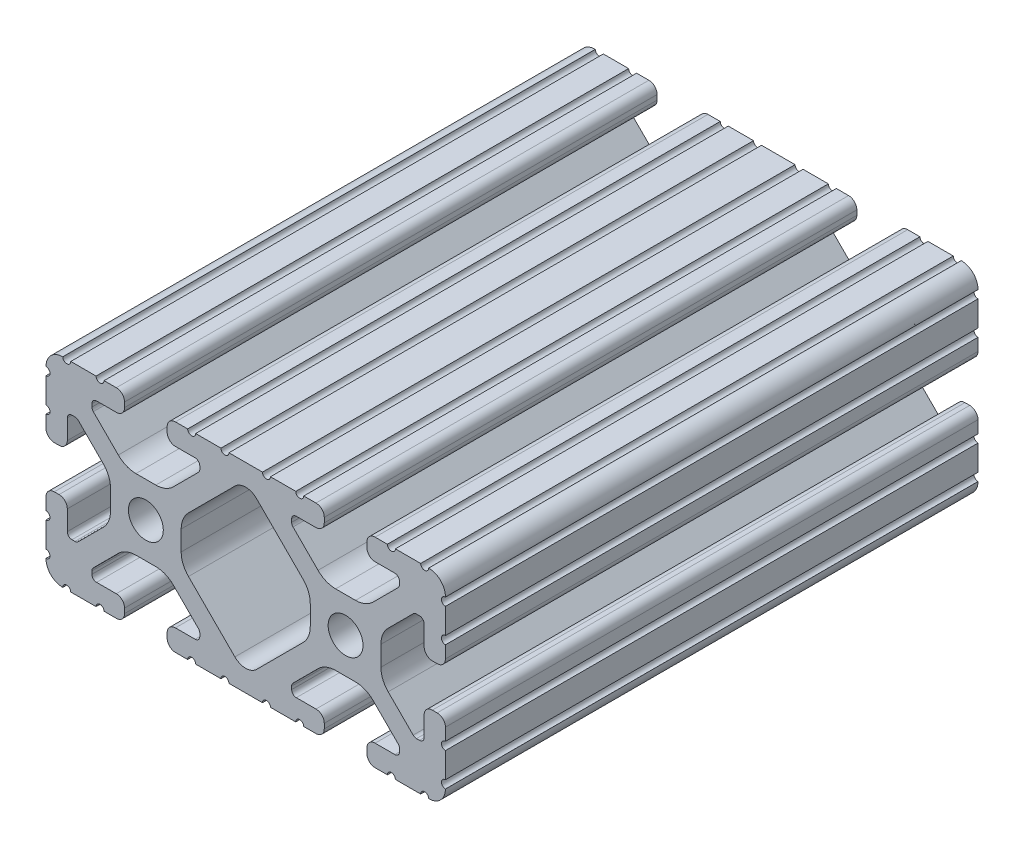
SolidWorks part; units mm, degrees
material "6105-T5 Aluminum"
ref_plane "Front Plane" through (0, 0, 0) normal (0, 0, 1) x (1, 0, 0)
ref_plane "Top Plane" through (0, 0, 0) normal (0, 1, 0) x (1, 0, 0)
ref_plane "Right Plane" through (0, 0, 0) normal (1, 0, 0) x (0, 0, -1)
sketch "Sketch1" plane through (0, 0, 0) normal (0, 0, 1) x (1, 0, 0)
  line L0 (-12.312, -1.8969) -> (-12.312, 1.8969)
  line L1 (-10.9208, 5.2555) -> (-2.0655, 14.1109)
  line L2 (2.0655, 14.1109) -> (10.9208, 5.2555)
  line L3 (12.312, 1.8969) -> (12.312, -1.8969)
  line L4 (10.9208, -5.2555) -> (2.0655, -14.1109)
  line L5 (-2.0655, -14.1109) -> (-10.9208, -5.2555)
  line L6 (38.1, -14.3256) -> (38.1, -9.4996)
  line L7 (38.1, -7.9756) -> (38.1, -5.6388)
  line L8 (36.5252, -4.064) -> (35.6108, -4.064)
  line L9 (34.036, -5.6388) -> (34.036, -9.398)
  line L10 (33.147, -10.287) -> (32.5789, -10.287)
  line L11 (31.9503, -10.0266) -> (27.1792, -5.2555)
  line L12 (25.788, -1.8969) -> (25.788, 1.8969)
  line L13 (27.1792, 5.2555) -> (31.9503, 10.0266)
  line L14 (32.5789, 10.287) -> (33.147, 10.287)
  line L15 (34.036, 9.398) -> (34.036, 5.6388)
  line L16 (35.6108, 4.064) -> (36.5252, 4.064)
  line L17 (38.1, 5.6388) -> (38.1, 7.9756)
  line L18 (38.1, 9.4996) -> (38.1, 14.3256)
  line L19 (38.1, 15.8496) -> (38.1, 15.875)
  line L20 (34.925, 19.05) -> (34.8996, 19.05)
  line L21 (33.3756, 19.05) -> (28.5496, 19.05)
  line L22 (27.0256, 19.05) -> (24.6888, 19.05)
  line L23 (23.114, 17.4752) -> (23.114, 16.5608)
  line L24 (24.6888, 14.986) -> (28.448, 14.986)
  line L25 (29.337, 14.097) -> (29.337, 13.5289)
  line L26 (29.0766, 12.9003) -> (24.3055, 8.1292)
  line L27 (20.9469, 6.738) -> (17.1531, 6.738)
  line L28 (13.7945, 8.1292) -> (9.0234, 12.9003)
  line L29 (8.763, 13.5289) -> (8.763, 14.097)
  line L30 (9.652, 14.986) -> (13.4112, 14.986)
  line L31 (14.986, 16.5608) -> (14.986, 17.4752)
  line L32 (13.4112, 19.05) -> (11.0744, 19.05)
  line L33 (9.5504, 19.05) -> (4.7244, 19.05)
  line L34 (3.2004, 19.05) -> (-3.2004, 19.05)
  line L35 (-4.7244, 19.05) -> (-9.5504, 19.05)
  line L36 (-11.0744, 19.05) -> (-13.4112, 19.05)
  line L37 (-14.986, 17.4752) -> (-14.986, 16.5608)
  line L38 (-13.4112, 14.986) -> (-9.652, 14.986)
  line L39 (-8.763, 14.097) -> (-8.763, 13.5289)
  line L40 (-9.0234, 12.9003) -> (-13.7945, 8.1292)
  line L41 (-17.1531, 6.738) -> (-20.9469, 6.738)
  line L42 (-24.3055, 8.1292) -> (-29.0766, 12.9003)
  line L43 (-29.337, 13.5289) -> (-29.337, 14.097)
  line L44 (-28.448, 14.986) -> (-24.6888, 14.986)
  line L45 (-23.114, 16.5608) -> (-23.114, 17.4752)
  line L46 (-24.6888, 19.05) -> (-27.0256, 19.05)
  line L47 (-28.5496, 19.05) -> (-33.3756, 19.05)
  line L48 (-34.8996, 19.05) -> (-34.925, 19.05)
  line L49 (-38.1, 15.875) -> (-38.1, 15.8496)
  line L50 (-38.1, 14.3256) -> (-38.1, 9.4996)
  line L51 (-38.1, 7.9756) -> (-38.1, 5.6388)
  line L52 (-36.5252, 4.064) -> (-35.6108, 4.064)
  line L53 (-34.036, 5.6388) -> (-34.036, 9.398)
  line L54 (-33.147, 10.287) -> (-32.5789, 10.287)
  line L55 (-31.9503, 10.0266) -> (-27.1792, 5.2555)
  line L56 (-25.788, 1.8969) -> (-25.788, -1.8969)
  line L57 (-27.1792, -5.2555) -> (-31.9503, -10.0266)
  line L58 (-32.5789, -10.287) -> (-33.147, -10.287)
  line L59 (-34.036, -9.398) -> (-34.036, -5.6388)
  line L60 (-35.6108, -4.064) -> (-36.5252, -4.064)
  line L61 (-38.1, -5.6388) -> (-38.1, -7.9756)
  line L62 (-38.1, -9.4996) -> (-38.1, -14.3256)
  line L63 (-38.1, -15.8496) -> (-38.1, -15.875)
  line L64 (-34.925, -19.05) -> (-34.8996, -19.05)
  line L65 (-33.3756, -19.05) -> (-28.5496, -19.05)
  line L66 (-27.0256, -19.05) -> (-24.6888, -19.05)
  line L67 (-23.114, -17.4752) -> (-23.114, -16.5608)
  line L68 (-24.6888, -14.986) -> (-28.448, -14.986)
  line L69 (-29.337, -14.097) -> (-29.337, -13.5289)
  line L70 (-29.0766, -12.9003) -> (-24.3055, -8.1292)
  line L71 (-20.9469, -6.738) -> (-17.1531, -6.738)
  line L72 (-13.7945, -8.1292) -> (-9.0234, -12.9003)
  line L73 (-8.763, -13.5289) -> (-8.763, -14.097)
  line L74 (-9.652, -14.986) -> (-13.4112, -14.986)
  line L75 (-14.986, -16.5608) -> (-14.986, -17.4752)
  line L76 (-13.4112, -19.05) -> (-11.0744, -19.05)
  line L77 (-9.5504, -19.05) -> (-4.7244, -19.05)
  line L78 (-3.2004, -19.05) -> (3.2004, -19.05)
  line L79 (4.7244, -19.05) -> (9.5504, -19.05)
  line L80 (11.0744, -19.05) -> (13.4112, -19.05)
  line L81 (14.986, -17.4752) -> (14.986, -16.5608)
  line L82 (13.4112, -14.986) -> (9.652, -14.986)
  line L83 (8.763, -14.097) -> (8.763, -13.5289)
  line L84 (9.0234, -12.9003) -> (13.7945, -8.1292)
  line L85 (17.1531, -6.738) -> (20.9469, -6.738)
  line L86 (24.3055, -8.1292) -> (29.0766, -12.9003)
  line L87 (29.337, -13.5289) -> (29.337, -14.097)
  line L88 (28.448, -14.986) -> (24.6888, -14.986)
  line L89 (23.114, -16.5608) -> (23.114, -17.4752)
  line L90 (24.6888, -19.05) -> (27.0256, -19.05)
  line L91 (28.5496, -19.05) -> (33.3756, -19.05)
  line L92 (34.8996, -19.05) -> (34.925, -19.05)
  line L93 (38.1, -15.875) -> (38.1, -15.8496)
  circle A0 centre (19.05, 0) radius 3.3274
  circle A1 centre (-19.05, 0) radius 3.3274
  arc A2 (-10.9208, 5.2555) -> (-12.312, 1.8969) centre (-7.5622, 1.8969) ccw
  arc A3 (2.0655, 14.1109) -> (-2.0655, 14.1109) centre (0, 12.0454) ccw
  arc A4 (12.312, 1.8969) -> (10.9208, 5.2555) centre (7.5622, 1.8969) ccw
  arc A5 (10.9208, -5.2555) -> (12.312, -1.8969) centre (7.5622, -1.8969) ccw
  arc A6 (-2.0655, -14.1109) -> (2.0655, -14.1109) centre (0, -12.0454) ccw
  arc A7 (-12.312, -1.8969) -> (-10.9208, -5.2555) centre (-7.5622, -1.8969) ccw
  arc A8 (38.1, -14.3256) -> (38.1, -15.8496) centre (38.1, -15.0876) ccw
  arc A9 (38.1, -7.9756) -> (38.1, -9.4996) centre (38.1, -8.7376) ccw
  arc A10 (38.1, -5.6388) -> (36.5252, -4.064) centre (36.5252, -5.6388) ccw
  arc A11 (35.6108, -4.064) -> (34.036, -5.6388) centre (35.6108, -5.6388) ccw
  arc A12 (33.147, -10.287) -> (34.036, -9.398) centre (33.147, -9.398) ccw
  arc A13 (31.9503, -10.0266) -> (32.5789, -10.287) centre (32.5789, -9.398) ccw
  arc A14 (25.788, -1.8969) -> (27.1792, -5.2555) centre (30.5378, -1.8969) ccw
  arc A15 (27.1792, 5.2555) -> (25.788, 1.8969) centre (30.5378, 1.8969) ccw
  arc A16 (32.5789, 10.287) -> (31.9503, 10.0266) centre (32.5789, 9.398) ccw
  arc A17 (34.036, 9.398) -> (33.147, 10.287) centre (33.147, 9.398) ccw
  arc A18 (34.036, 5.6388) -> (35.6108, 4.064) centre (35.6108, 5.6388) ccw
  arc A19 (36.5252, 4.064) -> (38.1, 5.6388) centre (36.5252, 5.6388) ccw
  arc A20 (38.1, 9.4996) -> (38.1, 7.9756) centre (38.1, 8.7376) ccw
  arc A21 (38.1, 15.8496) -> (38.1, 14.3256) centre (38.1, 15.0876) ccw
  arc A22 (38.1, 15.875) -> (34.925, 19.05) centre (34.925, 15.875) ccw
  arc A23 (33.3756, 19.05) -> (34.8996, 19.05) centre (34.1376, 19.05) ccw
  arc A24 (27.0256, 19.05) -> (28.5496, 19.05) centre (27.7876, 19.05) ccw
  arc A25 (24.6888, 19.05) -> (23.114, 17.4752) centre (24.6888, 17.4752) ccw
  arc A26 (23.114, 16.5608) -> (24.6888, 14.986) centre (24.6888, 16.5608) ccw
  arc A27 (29.337, 14.097) -> (28.448, 14.986) centre (28.448, 14.097) ccw
  arc A28 (29.0766, 12.9003) -> (29.337, 13.5289) centre (28.448, 13.5289) ccw
  arc A29 (20.9469, 6.738) -> (24.3055, 8.1292) centre (20.9469, 11.4878) ccw
  arc A30 (13.7945, 8.1292) -> (17.1531, 6.738) centre (17.1531, 11.4878) ccw
  arc A31 (8.763, 13.5289) -> (9.0234, 12.9003) centre (9.652, 13.5289) ccw
  arc A32 (9.652, 14.986) -> (8.763, 14.097) centre (9.652, 14.097) ccw
  arc A33 (13.4112, 14.986) -> (14.986, 16.5608) centre (13.4112, 16.5608) ccw
  arc A34 (14.986, 17.4752) -> (13.4112, 19.05) centre (13.4112, 17.4752) ccw
  arc A35 (9.5504, 19.05) -> (11.0744, 19.05) centre (10.3124, 19.05) ccw
  arc A36 (3.2004, 19.05) -> (4.7244, 19.05) centre (3.9624, 19.05) ccw
  arc A37 (-4.7244, 19.05) -> (-3.2004, 19.05) centre (-3.9624, 19.05) ccw
  arc A38 (-11.0744, 19.05) -> (-9.5504, 19.05) centre (-10.3124, 19.05) ccw
  arc A39 (-13.4112, 19.05) -> (-14.986, 17.4752) centre (-13.4112, 17.4752) ccw
  arc A40 (-14.986, 16.5608) -> (-13.4112, 14.986) centre (-13.4112, 16.5608) ccw
  arc A41 (-8.763, 14.097) -> (-9.652, 14.986) centre (-9.652, 14.097) ccw
  arc A42 (-9.0234, 12.9003) -> (-8.763, 13.5289) centre (-9.652, 13.5289) ccw
  arc A43 (-17.1531, 6.738) -> (-13.7945, 8.1292) centre (-17.1531, 11.4878) ccw
  arc A44 (-24.3055, 8.1292) -> (-20.9469, 6.738) centre (-20.9469, 11.4878) ccw
  arc A45 (-29.337, 13.5289) -> (-29.0766, 12.9003) centre (-28.448, 13.5289) ccw
  arc A46 (-28.448, 14.986) -> (-29.337, 14.097) centre (-28.448, 14.097) ccw
  arc A47 (-24.6888, 14.986) -> (-23.114, 16.5608) centre (-24.6888, 16.5608) ccw
  arc A48 (-23.114, 17.4752) -> (-24.6888, 19.05) centre (-24.6888, 17.4752) ccw
  arc A49 (-28.5496, 19.05) -> (-27.0256, 19.05) centre (-27.7876, 19.05) ccw
  arc A50 (-34.8996, 19.05) -> (-33.3756, 19.05) centre (-34.1376, 19.05) ccw
  arc A51 (-34.925, 19.05) -> (-38.1, 15.875) centre (-34.925, 15.875) ccw
  arc A52 (-38.1, 14.3256) -> (-38.1, 15.8496) centre (-38.1, 15.0876) ccw
  arc A53 (-38.1, 7.9756) -> (-38.1, 9.4996) centre (-38.1, 8.7376) ccw
  arc A54 (-38.1, 5.6388) -> (-36.5252, 4.064) centre (-36.5252, 5.6388) ccw
  arc A55 (-35.6108, 4.064) -> (-34.036, 5.6388) centre (-35.6108, 5.6388) ccw
  arc A56 (-33.147, 10.287) -> (-34.036, 9.398) centre (-33.147, 9.398) ccw
  arc A57 (-31.9503, 10.0266) -> (-32.5789, 10.287) centre (-32.5789, 9.398) ccw
  arc A58 (-25.788, 1.8969) -> (-27.1792, 5.2555) centre (-30.5378, 1.8969) ccw
  arc A59 (-27.1792, -5.2555) -> (-25.788, -1.8969) centre (-30.5378, -1.8969) ccw
  arc A60 (-32.5789, -10.287) -> (-31.9503, -10.0266) centre (-32.5789, -9.398) ccw
  arc A61 (-34.036, -9.398) -> (-33.147, -10.287) centre (-33.147, -9.398) ccw
  arc A62 (-34.036, -5.6388) -> (-35.6108, -4.064) centre (-35.6108, -5.6388) ccw
  arc A63 (-36.5252, -4.064) -> (-38.1, -5.6388) centre (-36.5252, -5.6388) ccw
  arc A64 (-38.1, -9.4996) -> (-38.1, -7.9756) centre (-38.1, -8.7376) ccw
  arc A65 (-38.1, -15.8496) -> (-38.1, -14.3256) centre (-38.1, -15.0876) ccw
  arc A66 (-38.1, -15.875) -> (-34.925, -19.05) centre (-34.925, -15.875) ccw
  arc A67 (-33.3756, -19.05) -> (-34.8996, -19.05) centre (-34.1376, -19.05) ccw
  arc A68 (-27.0256, -19.05) -> (-28.5496, -19.05) centre (-27.7876, -19.05) ccw
  arc A69 (-24.6888, -19.05) -> (-23.114, -17.4752) centre (-24.6888, -17.4752) ccw
  arc A70 (-23.114, -16.5608) -> (-24.6888, -14.986) centre (-24.6888, -16.5608) ccw
  arc A71 (-29.337, -14.097) -> (-28.448, -14.986) centre (-28.448, -14.097) ccw
  arc A72 (-29.0766, -12.9003) -> (-29.337, -13.5289) centre (-28.448, -13.5289) ccw
  arc A73 (-20.9469, -6.738) -> (-24.3055, -8.1292) centre (-20.9469, -11.4878) ccw
  arc A74 (-13.7945, -8.1292) -> (-17.1531, -6.738) centre (-17.1531, -11.4878) ccw
  arc A75 (-8.763, -13.5289) -> (-9.0234, -12.9003) centre (-9.652, -13.5289) ccw
  arc A76 (-9.652, -14.986) -> (-8.763, -14.097) centre (-9.652, -14.097) ccw
  arc A77 (-13.4112, -14.986) -> (-14.986, -16.5608) centre (-13.4112, -16.5608) ccw
  arc A78 (-14.986, -17.4752) -> (-13.4112, -19.05) centre (-13.4112, -17.4752) ccw
  arc A79 (-9.5504, -19.05) -> (-11.0744, -19.05) centre (-10.3124, -19.05) ccw
  arc A80 (-3.2004, -19.05) -> (-4.7244, -19.05) centre (-3.9624, -19.05) ccw
  arc A81 (4.7244, -19.05) -> (3.2004, -19.05) centre (3.9624, -19.05) ccw
  arc A82 (11.0744, -19.05) -> (9.5504, -19.05) centre (10.3124, -19.05) ccw
  arc A83 (13.4112, -19.05) -> (14.986, -17.4752) centre (13.4112, -17.4752) ccw
  arc A84 (14.986, -16.5608) -> (13.4112, -14.986) centre (13.4112, -16.5608) ccw
  arc A85 (8.763, -14.097) -> (9.652, -14.986) centre (9.652, -14.097) ccw
  arc A86 (9.0234, -12.9003) -> (8.763, -13.5289) centre (9.652, -13.5289) ccw
  arc A87 (17.1531, -6.738) -> (13.7945, -8.1292) centre (17.1531, -11.4878) ccw
  arc A88 (24.3055, -8.1292) -> (20.9469, -6.738) centre (20.9469, -11.4878) ccw
  arc A89 (29.337, -13.5289) -> (29.0766, -12.9003) centre (28.448, -13.5289) ccw
  arc A90 (28.448, -14.986) -> (29.337, -14.097) centre (28.448, -14.097) ccw
  arc A91 (24.6888, -14.986) -> (23.114, -16.5608) centre (24.6888, -16.5608) ccw
  arc A92 (23.114, -17.4752) -> (24.6888, -19.05) centre (24.6888, -17.4752) ccw
  arc A93 (28.5496, -19.05) -> (27.0256, -19.05) centre (27.7876, -19.05) ccw
  arc A94 (34.8996, -19.05) -> (33.3756, -19.05) centre (34.1376, -19.05) ccw
  arc A95 (34.925, -19.05) -> (38.1, -15.875) centre (34.925, -15.875) ccw
  dimension "D1" = 19.05
  dimension "D2" = 19.05
extrude "Boss-Extrude1" add sketch "Sketch1" along normal blind 101.6
